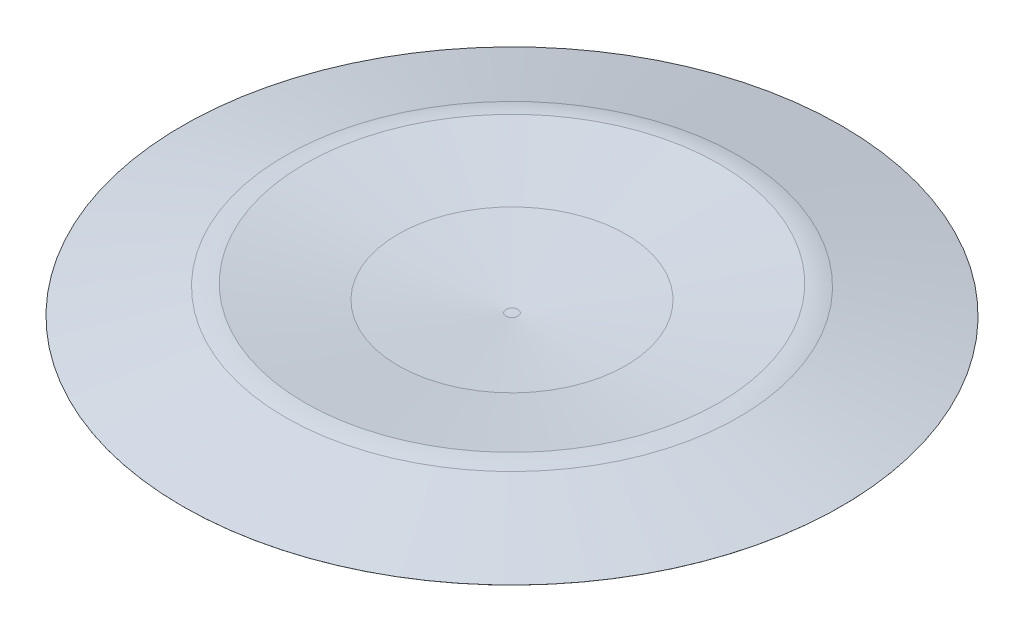
SolidWorks part; units mm, degrees
ref_plane "Piano frontale" through (0, 0, 0) normal (0, 0, 1) x (1, 0, 0)
ref_plane "Piano superiore" through (0, 0, 0) normal (0, 1, 0) x (1, 0, 0)
ref_plane "Piano destro" through (0, 0, 0) normal (1, 0, 0) x (0, 0, -1)
sketch "Schizzo1" plane through (0, 0, 0) normal (0, 0, 1) x (-1, 0, 0)
  line L0 (-554.6945, -544.7554) -> (-379.9955, -588.1202)
  line L1 (-346.6941, -592.7624) -> (-188.5588, -568.4062)
  line L3 (-188.5588, -568.4062) -> (-5.145, -549.4585)
  line L4 (-5.145, -549.4585) -> (4.8425, -549.4585)
  line L6 (-554.7186, -544.8525) -> (-380.0199, -588.2172)
  line L7 (-346.6879, -592.8626) -> (-188.5461, -568.5054)
  line L8 (-188.5461, -568.5054) -> (-5.1399, -549.5585)
  line L9 (-5.1399, -549.5585) -> (4.8425, -549.5585)
  line L10 (-554.6945, -544.7554) -> (-554.7186, -544.8525)
  line L11 (4.8425, -549.4585) -> (4.8425, -549.5585)
  line L12 (4.8425, -549.2399) -> (4.8425, -549.7444) construction
  arc A2 (-379.9955, -588.1202) -> (-346.6941, -592.7624) centre (-342.4879, -440.8206) ccw
  arc A3 (-380.0199, -588.2172) -> (-346.6879, -592.8626) centre (-342.4879, -440.8206) ccw
  dimension "D1" = 160
  dimension "D3" = 183.4138
  dimension "D2" = 0.1
revolve "Rivoluzione1" add sketch "Schizzo1" angle 360 about L12
